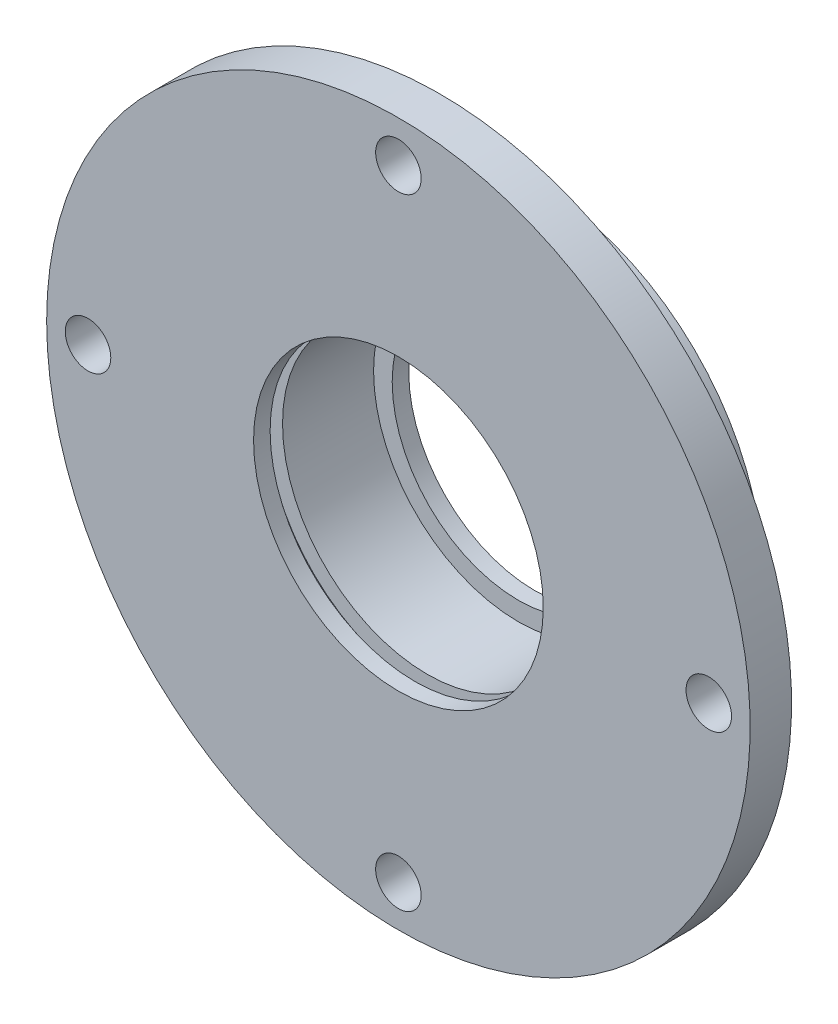
SolidWorks part; units mm, degrees
ref_plane "Front Plane" through (0, 0, 0) normal (0, 0, 1) x (1, 0, 0)
ref_plane "Top Plane" through (0, 0, 0) normal (0, 1, 0) x (1, 0, 0)
ref_plane "Right Plane" through (0, 0, 0) normal (1, 0, 0) x (0, 0, -1)
sketch "Sketch1" plane through (0, 0, 0) normal (0, 1, 0) x (1, 0, 0)
  line L0 (0, 30.507) -> (0, -29.2253) construction
sketch "Sketch2" plane through (0, 0, 0) normal (0, 1, 0) x (1, 0, 0)
  line L0 (17.5, -7) -> (42.5, -7)
  line L1 (42.5, -7) -> (42.5, -2)
  line L2 (42.5, -2) -> (22.5, -2)
  line L3 (22.5, -2) -> (22.5, 2)
  line L4 (22.5, 2) -> (27.5, 2)
  line L5 (27.5, 2) -> (27.5, 9.5)
  line L6 (27.5, 9.5) -> (15.25, 9.5)
  line L8 (0, 0) -> (22.5, 0) construction
  line L9 (0, 200030.507) -> (0, -200029.2253) construction
  line L10 (15.25, 9.5) -> (15.25, 7.5)
  line L11 (15.25, 7.5) -> (17.5, 7.5)
  line L12 (17.5, 7.5) -> (17.5, -7)
  dimension "D1" = 42.5
  dimension "D2" = 17.5
  dimension "D3" = 15.25
  dimension "D4" = 27.5
  dimension "D5" = 2
  dimension "D6" = 5
  dimension "D7" = 4
  dimension "D8" = 16.5
  dimension "D9" = 22.5
revolve "Revolve1" add sketch "Sketch2" angle 360 about L0
sketch "Sketch3" plane through (0, 0, 0) normal (0, 0, 1) x (1, 0, 0)
  line L0 (0, 0) -> (0, 34.75) construction
  line L1 (0, 34.75) -> (0, 37.5) construction
  line L2 (0, 37.5) -> (0, 40.25) construction
  line L3 (0, 40.25) -> (0, 42.5) construction
  circle A0 centre (0, 37.5) radius 2.75
  circle A1 centre (0, 0) radius 42.5 construction
  circle A2 centre (37.5, 0) radius 2.75
  circle A3 centre (0, -37.5) radius 2.75
  circle A4 centre (-37.5, 0) radius 2.75
  point P18 (0, 0)
  dimension "D1" = 5.5
  dimension "D2" = 2.25
  dimension "D3" = 4
extrude "Cut-Extrude2" cut sketch "Sketch3" along normal through all
sketch "Sketch4" plane through (0, 0, 0) normal (0, 1, 0) x (1, 0, 0)
  line L0 (0, -3.5) -> (19.5, -3.5)
  line L1 (0, 200030.507) -> (0, -200029.2253) construction
  line L2 (19.5, -3.5) -> (19.5, -5)
  line L3 (19.5, -5) -> (0, -5)
  line L4 (0, -5) -> (0, -3.5)
  line L5 (-42.5, -7) -> (42.5, -7) construction
  line L7 (17.5, -3.5) -> (17.5, -5) construction
  dimension "D1" = 2
  dimension "D2" = 1.5
  dimension "D3" = 17.5
  dimension "D4" = 2
revolve "Cut-Revolve1" cut sketch "Sketch4" angle 360 about L0
